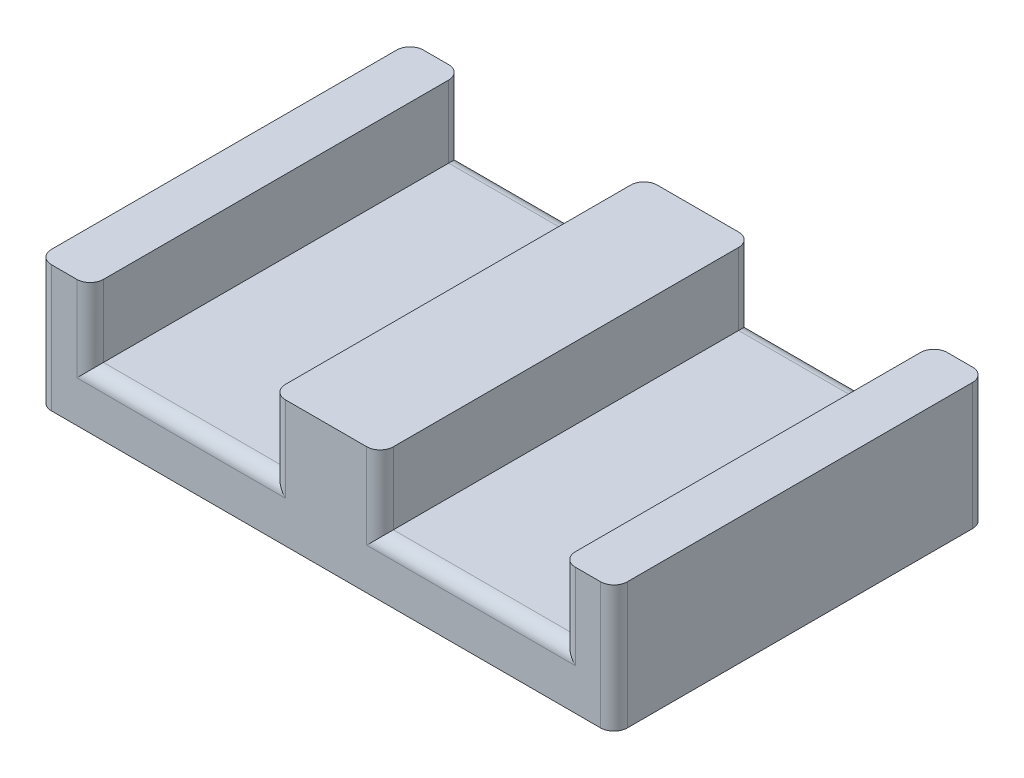
SolidWorks part; units mm, degrees
ref_plane "Спереди" through (0, 0, 0) normal (0, 0, 1) x (1, 0, 0)
ref_plane "Сверху" through (0, 0, 0) normal (0, 1, 0) x (1, 0, 0)
ref_plane "Справа" through (0, 0, 0) normal (1, 0, 0) x (0, 0, -1)
sketch "Эскиз1" plane through (0, 0, 0) normal (0, 1, 0) x (1, 0, 0)
  line L1 (-21.6, -13.95) -> (21.6, -13.95)
  line L2 (-21.6, -13.95) -> (-21.6, 13.95)
  line L3 (-21.6, 13.95) -> (21.6, 13.95)
  line L4 (21.6, -13.95) -> (21.6, 13.95)
  line L5 (-21.6, -13.95) -> (21.6, 13.95) construction
  line L6 (-21.6, 13.95) -> (21.6, -13.95) construction
  point P0 (0, 0)
extrude "Бобышка-Вытянуть1" add sketch "Эскиз1" along normal blind 4.1
sketch "Эскиз2" plane through (0, 4.1, 0) normal (0, 1, 0) x (1, 0, 0)
  line L0 (-21.6, -13.95) -> (21.6, -13.95) construction
  line L1 (-4.05, 13.95) -> (4.05, 13.95)
  line L2 (-4.05, 13.95) -> (-4.05, -13.95)
  line L3 (-4.05, -13.95) -> (4.05, -13.95)
  line L4 (4.05, 13.95) -> (4.05, -13.95)
  line L5 (-4.05, 13.95) -> (4.05, -13.95) construction
  line L6 (-4.05, -13.95) -> (4.05, 13.95) construction
  line L7 (21.6, 13.95) -> (-21.6, 13.95) construction
  line L8 (-21.6, -13.95) -> (-17.7, -13.95)
  line L9 (-21.6, -13.95) -> (-21.6, 13.95)
  line L10 (-21.6, 13.95) -> (-17.7, 13.95)
  line L11 (-17.7, -13.95) -> (-17.7, 13.95)
  line L13 (21.6, -13.95) -> (17.7, -13.95)
  line L14 (21.6, -13.95) -> (21.6, 13.95)
  line L15 (21.6, 13.95) -> (17.7, 13.95)
  line L16 (17.7, -13.95) -> (17.7, 13.95)
  point P0 (0, 0)
  dimension "D1" = 8.1
  dimension "D2" = 3.9
  dimension "D3" = 3.9
extrude "Бобышка-Вытянуть2" add sketch "Эскиз2" along normal blind 5.4
fillet "Скругление1" radius 1 16 edges at (10.875, 4.1, 13.95) (10.875, 4.1, -13.95) (-10.875, 4.1, -13.95) (-10.875, 4.1, 13.95) (21.6, 4.75, 13.95) (21.6, 4.75, -13.95) (17.7, 6.8, -13.95) (17.7, 6.8, 13.95) (4.05, 6.8, 13.95) (4.05, 6.8, -13.95) (-17.7, 6.8, 13.95) (-17.7, 6.8, -13.95) (-4.05, 6.8, -13.95) (-4.05, 6.8, 13.95) (-21.6, 4.75, -13.95) (-21.6, 4.75, 13.95)
